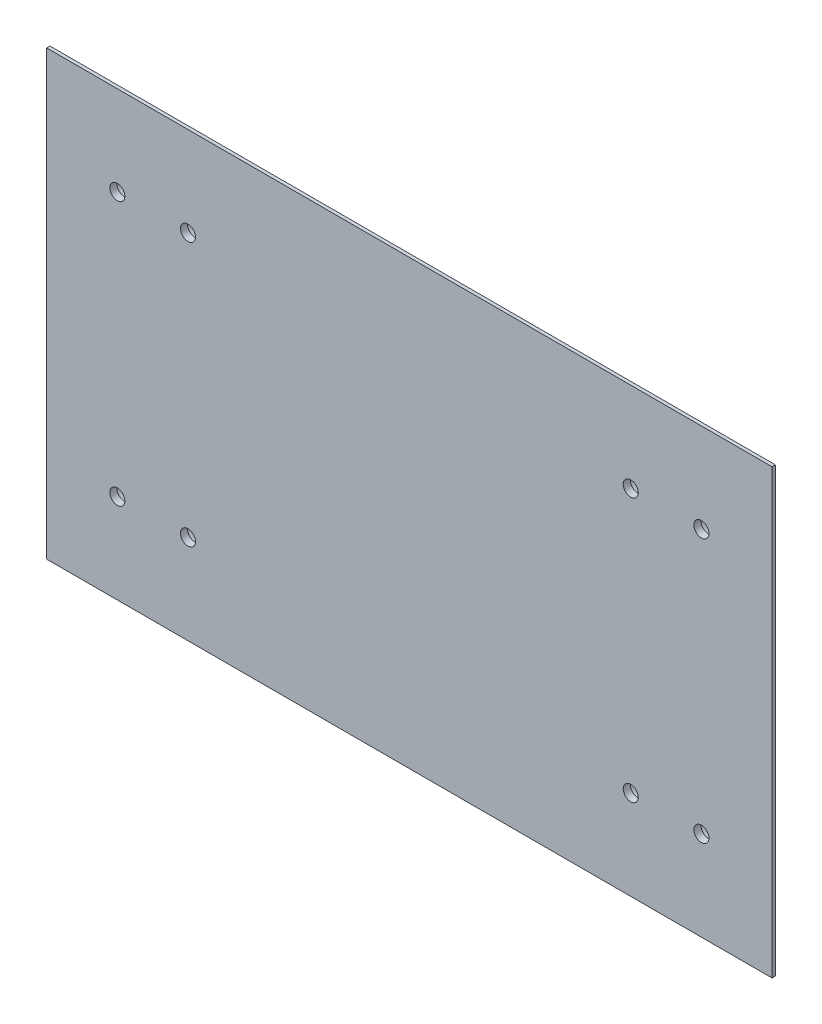
SolidWorks part; units mm, degrees
ref_plane "Front" through (0, 0, 0) normal (0, 0, 1) x (1, 0, 0)
ref_plane "Top" through (0, 0, 0) normal (0, 1, 0) x (1, 0, 0)
ref_plane "Right" through (0, 0, 0) normal (1, 0, 0) x (0, 0, -1)
sketch "Sketch1" plane through (0, 0, 0) normal (0, 0, 1) x (1, 0, 0)
  line L1 (70, -40) -> (-70, -40)
  line L2 (70, -40) -> (70, 40)
  line L3 (70, 40) -> (-70, 40)
  line L4 (-70, -40) -> (-70, 40)
  line L5 (70, -40) -> (-70, 40) construction
  line L6 (70, 40) -> (-70, -40) construction
  point P0 (0, 0)
  dimension "D1" = 140
  dimension "D2" = 80
extrude "Boss-Extrude1" add sketch "Sketch1" along normal blind 6
sketch "Sketch2" plane through (0, 0, 6) normal (0, 0, 1) x (1, 0, 0)
  line L0 (0, 0) -> (11.1446, 0)
  line L1 (11.1446, 0) -> (0, 0)
  line L2 (0, 0) -> (0, 18.2119)
  line L3 (-70, 40) -> (-70, -40) construction
  circle A0 centre (-62, 28) radius 1.6
  circle A1 centre (-47, 28) radius 1.6
  circle A2 centre (-47, -28) radius 1.6
  circle A3 centre (-62, -28) radius 1.6
  circle A4 centre (47, -28) radius 1.6
  circle A5 centre (62, -28) radius 1.6
  circle A6 centre (47, 28) radius 1.6
  circle A7 centre (62, 28) radius 1.6
  dimension "D4" = 3.2
  dimension "D1" = 15
  dimension "D2" = 28
  dimension "D3" = 8
extrude "Cut-Extrude1" cut sketch "Sketch2" against normal through all contours A0 | A1 | A6 | A7 | A4 | A5 | A3 | A2
sketch "Sketch3" plane through (0, 0, 0) normal (0, 0, -1) x (-1, 0, 0)
  circle A0 centre (62, 28) radius 3.5
  circle A1 centre (47, 28) radius 3.5
  circle A2 centre (-47, 28) radius 3.5
  circle A3 centre (-62, 28) radius 3.5
  circle A4 centre (-47, -28) radius 3.5
  circle A5 centre (-62, -28) radius 3.5
  circle A6 centre (62, -28) radius 3.5
  circle A7 centre (47, -28) radius 3.5
  dimension "D1" = 7
  dimension "D2" = 2
  dimension "D3" = 2
extrude "Cut-Extrude2" cut sketch "Sketch3" against normal blind 4.5
sketch "Sketch4" plane through (0, 0, 6) normal (0, 0, 1) x (1, 0, 0)
  line L0 (-77, 47) -> (77, 47)
  line L1 (-70, -40) -> (70, -40)
  line L2 (-70, -40) -> (-70, 40)
  line L3 (-70, 40) -> (70, 40)
  line L4 (70, -40) -> (70, 40)
  line L5 (-70, -40) -> (70, 40) construction
  line L6 (-70, 40) -> (70, -40) construction
  line L7 (77, -47) -> (77, 47)
  line L8 (-77, -47) -> (77, -47)
  line L9 (-77, -47) -> (-77, 47)
  point P0 (0, 0)
  dimension "D1" = 7
extrude "Boss-Extrude2" add sketch "Sketch4" against normal blind 0.7
